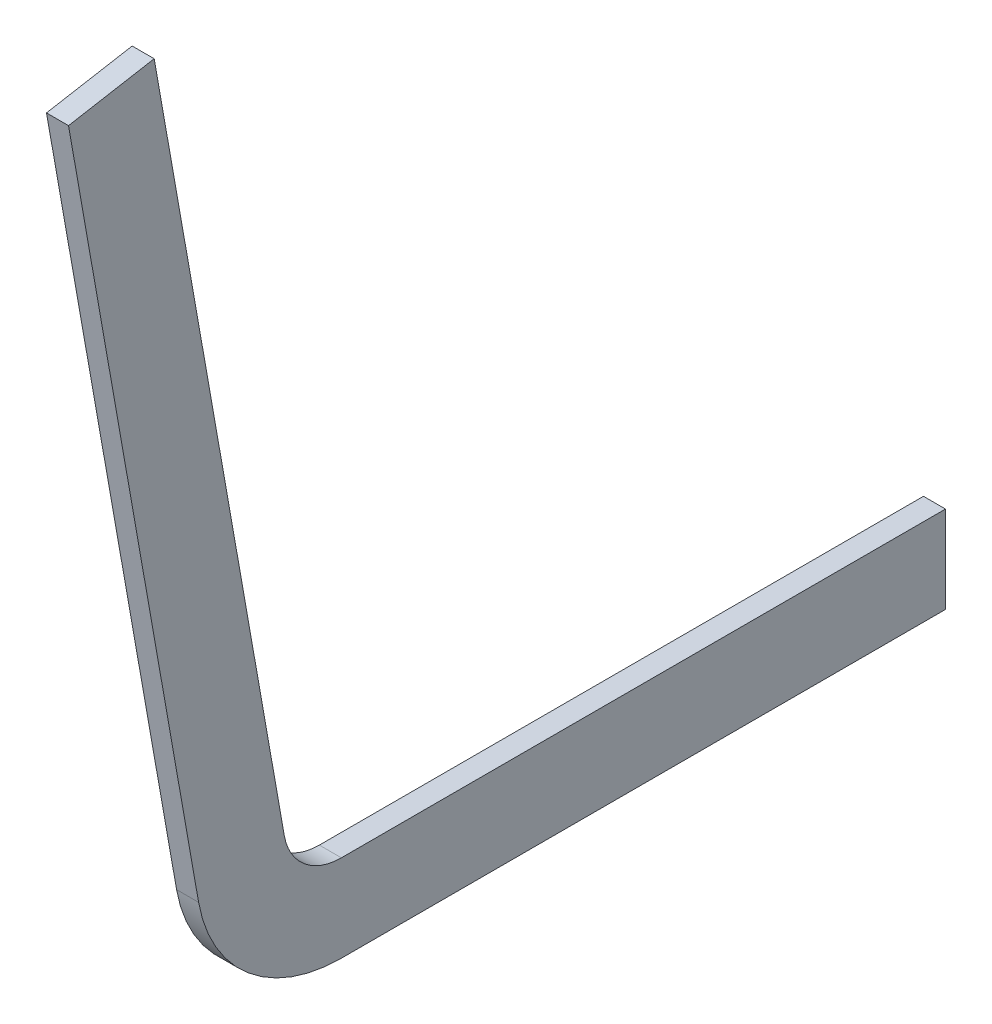
SolidWorks part; units mm, degrees
ref_plane "Front" through (0, 0, 0) normal (0, 0, 1) x (1, 0, 0)
ref_plane "Top" through (0, 0, 0) normal (0, 1, 0) x (1, 0, 0)
ref_plane "Right" through (0, 0, 0) normal (1, 0, 0) x (0, 0, -1)
sketch "Sketch1" plane through (0, 0, 0) normal (1, 0, 0) x (0, 0, -1)
  line L8 (-84.1955, -182.4) -> (-80, -182.4)
  line L9 (-131.2503, -34.5085) -> (-108.8157, -161.7412)
  line L10 (-116.4781, -31.9038) -> (-131.2503, -34.5085)
  line L11 (-94.0436, -159.1365) -> (-116.4781, -31.9038)
  line L12 (-80, -167.4) -> (-84.1955, -167.4)
  line L13 (20, -167.4) -> (-80, -167.4)
  line L14 (20, -182.4) -> (20, -167.4)
  line L15 (-80, -182.4) -> (20, -182.4)
  line L16 (-84.1955, -182.4) -> (-80, -182.4)
  line L17 (-131.2503, -34.5085) -> (-108.8157, -161.7412)
  line L18 (-116.4781, -31.9038) -> (-131.2503, -34.5085)
  line L19 (-94.0436, -159.1365) -> (-116.4781, -31.9038)
  line L20 (-80, -167.4) -> (-84.1955, -167.4)
  line L21 (20, -167.4) -> (-80, -167.4)
  line L22 (20, -182.4) -> (20, -167.4)
  line L23 (-80, -182.4) -> (20, -182.4)
  arc A2 (-108.8157, -161.7412) -> (-84.1955, -182.4) centre (-84.1955, -157.4) ccw
  arc A3 (-94.0436, -159.1365) -> (-84.1955, -167.4) centre (-84.1955, -157.4) ccw
  arc A4 (-108.8157, -161.7412) -> (-84.1955, -182.4) centre (-84.1955, -157.4) ccw
  arc A5 (-94.0436, -159.1365) -> (-84.1955, -167.4) centre (-84.1955, -157.4) ccw
  dimension "D1" = 0
extrude "Boss-Extrude1" add sketch "Sketch1" along normal mid plane 3.8
